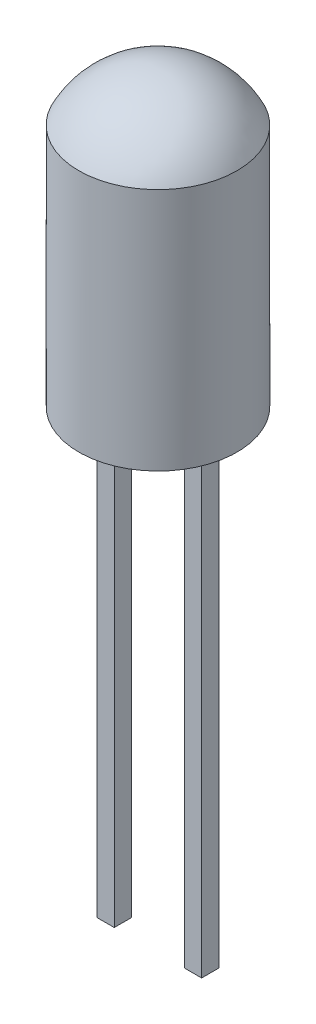
SolidWorks part; units mm, degrees
ref_plane "Alzado" through (0, 0, 0) normal (0, 0, 1) x (1, 0, 0)
ref_plane "Planta" through (0, 0, 0) normal (0, 1, 0) x (1, 0, 0)
ref_plane "Vista lateral" through (0, 0, 0) normal (1, 0, 0) x (0, 0, -1)
sketch "Croquis1" plane through (0, 0, 0) normal (0, 0, 1) x (1, 0, 0)
  line L0 (0, 0) -> (2.2992, 0)
  line L1 (2.2992, 0) -> (2.2992, 7.0842)
  line L3 (0, 8.5) -> (0, 0)
  arc A0 (0, 8.5) -> (2.2992, 7.0842) centre (0, 5.9252) cw
revolve "Revolución1" add sketch "Croquis1" angle 360 about L3
sketch "Croquis2" plane through (0, 0, 0) normal (0, -1, 0) x (1, 0, 0)
  line L0 (1.27, 0) -> (-1.2689, 0) construction
  line L1 (0, 1.092) -> (0, -0.8885) construction
  line L2 (1.52, 0.25) -> (1.02, 0.25)
  line L3 (1.52, 0.25) -> (1.52, -0.25)
  line L4 (1.52, -0.25) -> (1.02, -0.25)
  line L5 (1.02, 0.25) -> (1.02, -0.25)
  line L6 (1.52, 0.25) -> (1.02, -0.25) construction
  line L7 (1.52, -0.25) -> (1.02, 0.25) construction
  line L8 (-1.52, 0.25) -> (-1.02, 0.25)
  line L9 (-1.52, 0.25) -> (-1.52, -0.25)
  line L10 (-1.52, -0.25) -> (-1.02, -0.25)
  line L11 (-1.02, 0.25) -> (-1.02, -0.25)
  point P11 (0, 0)
extrude "Saliente-Extruir1" add sketch "Croquis2" along normal blind 13.5
